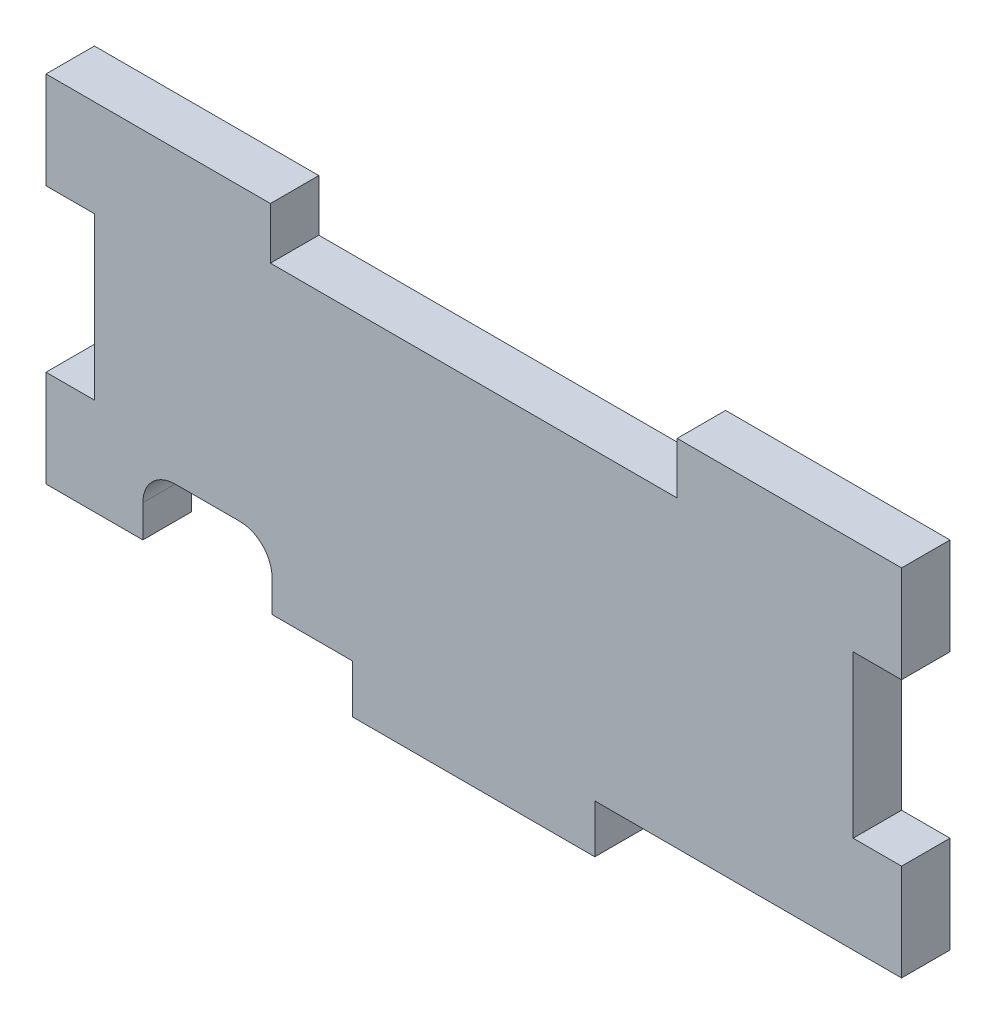
SolidWorks part; units mm, degrees
material "ABS PC"
ref_plane "Front Plane" through (0, 0, 0) normal (0, 0, 1) x (1, 0, 0)
ref_plane "Top Plane" through (0, 0, 0) normal (0, 1, 0) x (1, 0, 0)
ref_plane "Right Plane" through (0, 0, 0) normal (1, 0, 0) x (0, 0, -1)
sketch "Sketch1" plane through (0, 0, 0) normal (0, 0, 1) x (1, 0, 0)
  line L0 (-20, -11) -> (20, -11)
  line L1 (-54, 11) -> (54, 11)
  line L2 (-54, 11) -> (-54, -11)
  line L3 (-54, -11) -> (-35, -11)
  line L4 (54, 11) -> (54, -11)
  line L5 (35, -11) -> (54, -11)
  line L6 (-35, -11) -> (-35, -14)
  line L7 (-35, -14) -> (-20, -14)
  line L8 (-20, -11) -> (-20, -14)
  line L9 (0, 11) -> (0, 0) construction
  line L10 (20, -11) -> (20, -14)
  line L11 (20, -14) -> (35, -14)
  line L12 (35, -11) -> (35, -14)
  line L13 (0, 0) -> (0, -11) construction
  dimension "D1" = 22
  dimension "D2" = 108
  dimension "D3" = 15
  dimension "D4" = 3
  dimension "D5" = 40
extrude "Boss-Extrude1" add sketch "Sketch1" along normal mid plane 3 contours L1 L4 L5 L12 L11 L10 L0 L8 L7 L6 L3 L2
sketch "Sketch2" plane through (0, 0, 1.5) normal (0, 0, 1) x (1, 0, 0)
  line L0 (54, -5) -> (54, 5) construction
  line L1 (1, 5) -> (4, 5)
  line L2 (1, 5) -> (1, -5)
  line L3 (1, -5) -> (4, -5)
  line L4 (4, 5) -> (4, -5)
  line L5 (51, 5) -> (54, 5)
  line L6 (51, 5) -> (51, -5)
  line L7 (51, -5) -> (54, -5)
  line L8 (54, 5) -> (54, -5)
  line L9 (0, 0) -> (1, 0) construction
  dimension "D1" = 3
  dimension "D2" = 47
  dimension "D3" = 10
extrude "Cut-Extrude1" cut sketch "Sketch2" against normal through all
sketch "Sketch3" plane through (0, 0, 1.5) normal (0, 0, 1) x (1, 0, 0)
  line L0 (1, 5) -> (1, -5) construction
  line L1 (-54, 11) -> (1, 11)
  line L2 (-54, 11) -> (-54, -14)
  line L3 (-54, -14) -> (1, -14)
  line L4 (1, 11) -> (1, -14)
  line L5 (-35, -14) -> (-20, -14) construction
extrude "Cut-Extrude2" cut sketch "Sketch3" against normal through all
sketch "Sketch4" plane through (0, 0, -1.5) normal (0, 0, -1) x (-1, 0, 0)
  line L0 (-7, -11) -> (-7, -9)
  line L1 (-1, -11) -> (-20, -11) construction
  line L2 (-9, -7) -> (-13, -7)
  line L3 (-15, -9) -> (-15, -11)
  line L4 (-7, -11) -> (-15, -11)
  line L5 (-20, -11) -> (-20, -14) construction
  arc A0 (-15, -9) -> (-13, -7) centre (-13, -9) cw
  arc A1 (-9, -7) -> (-7, -9) centre (-9, -9) cw
  dimension "D1" = 2
  dimension "D2" = 4
  dimension "D3" = 8
  dimension "D4" = 5
extrude "Cut-Extrude3" cut sketch "Sketch4" against normal through all
sketch "Sketch5" plane through (0, 0, 1.5) normal (0, 0, 1) x (1, 0, 0)
  line L0 (25, 11) -> (25, 6)
  line L1 (1, 11) -> (54, 11) construction
  line L2 (25, 6) -> (23.5, 6)
  line L3 (23.5, 6) -> (23.5, 2)
  line L4 (23.5, 2) -> (25, 2)
  line L5 (25, 2) -> (25, -3)
  line L6 (25, -3) -> (30, -3)
  line L7 (30, -3) -> (30, 2)
  line L8 (30, 2) -> (31.5, 2)
  line L9 (31.5, 2) -> (31.5, 6)
  line L10 (31.5, 6) -> (30, 6)
  line L11 (30, 6) -> (30, 11)
  line L12 (30, 11) -> (25, 11)
  line L13 (27.5, -3) -> (27.5, -14) construction
  line L14 (20, -14) -> (35, -14) construction
  dimension "D1" = 5
  dimension "D2" = 8
  dimension "D3" = 5
  dimension "D4" = 5
  dimension "D5" = 4
extrude "Cut-Extrude4" [suppressed] cut sketch "Sketch5" against normal through all
sketch "Sketch6" [suppressed] plane through (0, 0, 1.5) normal (0, 0, 1) x (1, 0, 0)
  line L1 (20, -11) -> (35, -11)
  line L2 (20, -11) -> (20, -14)
  line L3 (20, -14) -> (35, -14)
  line L4 (35, -11) -> (35, -14)
extrude "Cut-Extrude5" [suppressed] cut sketch "Sketch6" against normal through all
ref_plane "Plane1" through (27.5, 0, 0) normal (1, 0, 0) x (0, 0, -1)
sketch "Sketch7" plane through (0, 0, 1.5) normal (0, 0, 1) x (1, 0, 0)
  line L0 (1, 11) -> (54, 11) construction
  line L1 (14.9, 11) -> (40.1, 11)
  line L2 (14.9, 11) -> (14.9, 7.8)
  line L3 (14.9, 7.8) -> (40.1, 7.8)
  line L4 (40.1, 11) -> (40.1, 7.8)
  line L5 (27.5, -14) -> (27.5, 7.8) construction
  line L6 (20, -14) -> (35, -14) construction
  dimension "D1" = 25.2
  dimension "D2" = 3.2
extrude "Cut-Extrude6" cut sketch "Sketch7" against normal through all
